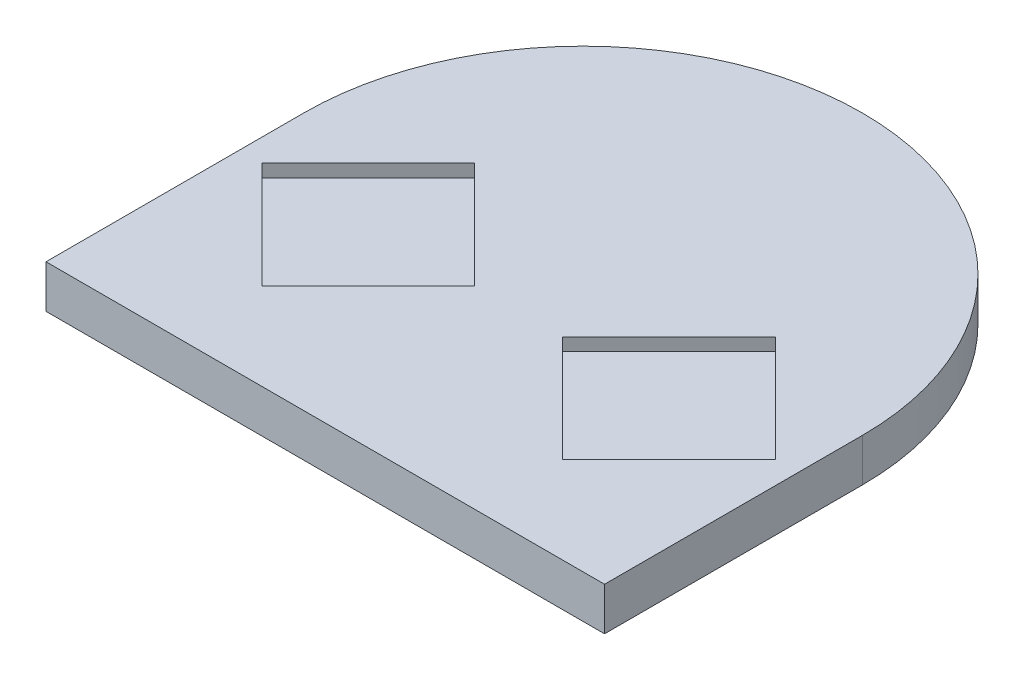
SolidWorks part; units mm, degrees
ref_plane "前视基准面" through (0, 0, 0) normal (0, 0, 1) x (1, 0, 0)
ref_plane "上视基准面" through (0, 0, 0) normal (0, 1, 0) x (1, 0, 0)
ref_plane "右视基准面" through (0, 0, 0) normal (1, 0, 0) x (0, 0, -1)
sketch "草图1" plane through (0, 0, 0) normal (0, 1, 0) x (1, 0, 0)
  line L0 (0, 0) -> (0, -60)
  line L1 (0, -60) -> (130, -60)
  line L2 (130, -60) -> (130, 0)
  line L3 (0, 0) -> (130, 0) construction
  arc A0 (0, 0) -> (130, 0) centre (65, 0) cw
  dimension "D1" = 60
  dimension "D2" = 130
extrude "凸台-拉伸1" add sketch "草图1" along normal blind 10
sketch "草图2" plane through (0, 10, 0) normal (0, 1, 0) x (1, 0, 0)
  line L0 (65, 65) -> (65, -60) construction
  line L1 (0, -60) -> (130, -60) construction
  line L2 (5.2513, -15) -> (30, -39.7487)
  line L3 (5.2513, -15) -> (30, 9.7487)
  line L4 (30, -39.7487) -> (54.7487, -15)
  line L5 (30, 9.7487) -> (54.7487, -15)
  line L6 (5.2513, -15) -> (54.7487, -15) construction
  line L7 (30, -39.7487) -> (30, 9.7487) construction
  line L8 (100, -39.7487) -> (100, 9.7487) construction
  line L9 (124.7487, -15) -> (75.2513, -15) construction
  line L10 (100, 9.7487) -> (75.2513, -15)
  line L11 (100, -39.7487) -> (75.2513, -15)
  line L12 (124.7487, -15) -> (100, 9.7487)
  line L13 (124.7487, -15) -> (100, -39.7487)
  arc A0 (130, 0) -> (0, 0) centre (65, 0) ccw construction
  point P8 (30, -15)
  point P16 (100, -15)
  dimension "D1" = 35
  dimension "D2" = 35
  dimension "D3" = 45
extrude "切除-拉伸1" cut sketch "草图2" against normal blind 3
